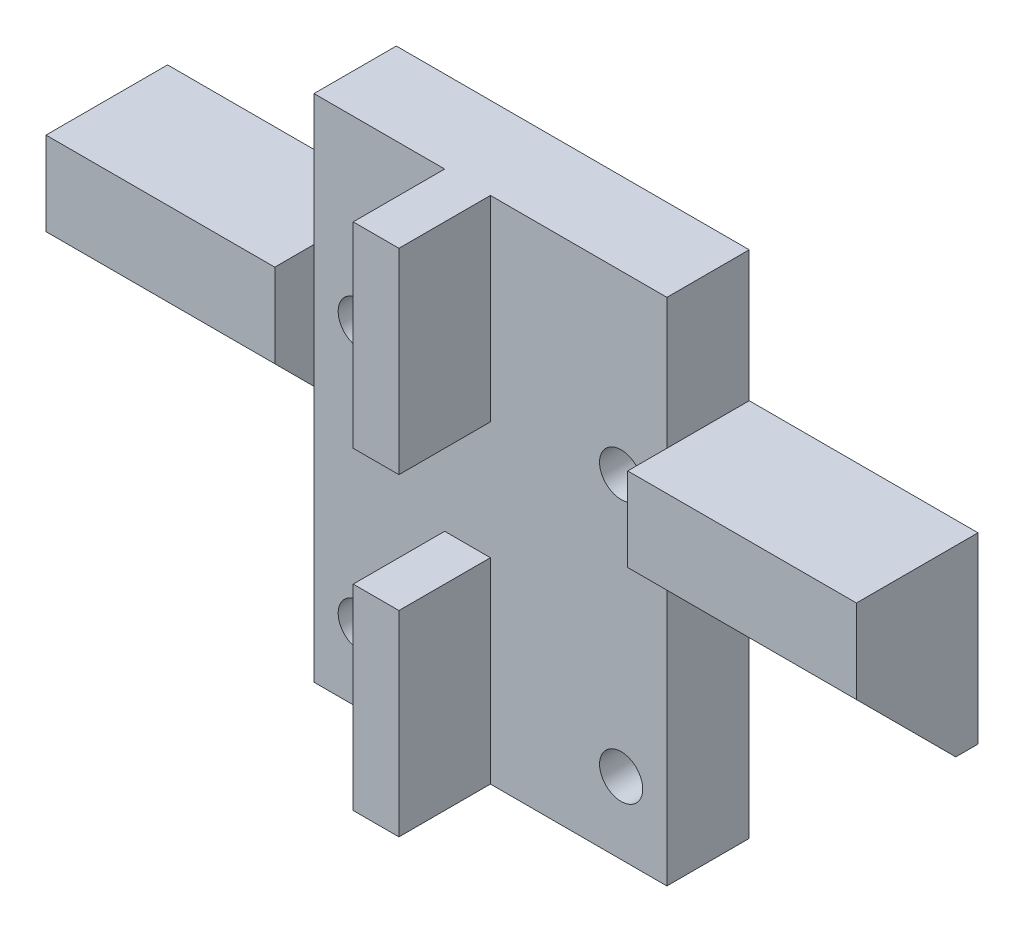
SolidWorks part; units mm, degrees
material "3.1355 (EN-AW 2024)"
ref_plane "Front" through (0, 0, 0) normal (0, 0, 1) x (1, 0, 0)
ref_plane "Top" through (0, 0, 0) normal (0, 1, 0) x (1, 0, 0)
ref_plane "Right" through (0, 0, 0) normal (1, 0, 0) x (0, 0, -1)
sketch "Эскиз1" plane through (0, 0, 0) normal (0, 0, 1) x (1, 0, 0)
  line L0 (-13.5, 23.5) -> (13.5, 23.5)
  line L1 (13.5, 23.5) -> (13.5, 13.5)
  line L2 (13.5, 13.5) -> (31, 13.5)
  line L3 (31, 13.5) -> (31, -0.5)
  line L4 (31, -0.5) -> (13.5, -0.5)
  line L5 (13.5, -0.5) -> (13.5, -15.5)
  line L6 (13.5, -15.5) -> (-13.5, -15.5)
  line L7 (-13.5, -15.5) -> (-13.5, -0.5)
  line L8 (-13.5, -0.5) -> (-31, -0.5)
  line L9 (-31, -0.5) -> (-31, 13.5)
  line L10 (-31, 13.5) -> (-13.5, 13.5)
  line L11 (-13.5, 13.5) -> (-13.5, 23.5)
  line L12 (-10, 10) -> (0, 10) construction
  line L13 (0, 10) -> (10, 10) construction
  line L14 (10, 10) -> (10, 0) construction
  line L15 (10, 0) -> (10, -10) construction
  circle A0 centre (-10, 10) radius 1.65
  circle A1 centre (10, 10) radius 1.65
  circle A2 centre (10, -10) radius 1.65
  circle A3 centre (-10, -10) radius 1.65
  point P12 (0, 23.5)
  point P14 (0, -15.5)
  dimension "D1" = 3.3
  dimension "D2" = 20
  dimension "D3" = 20
  dimension "D4" = 27
  dimension "D5" = 62
  dimension "D6" = 14
  dimension "D7" = 15
  dimension "D8" = 39
  dimension "D9" = 5.5
extrude "База" add sketch "Эскиз1" along normal blind 13.3
sketch "Эскиз2" plane through (0, 0, 13.3) normal (0, 0, 1) x (1, 0, 0)
  line L0 (0, 23.5) -> (13.5, 23.5)
  line L1 (13.5, 23.5) -> (-13.5, 23.5) construction
  line L2 (13.5, 23.5) -> (13.5, -15.5)
  line L3 (13.5, -15.5) -> (0, -15.5)
  line L4 (-13.5, -15.5) -> (13.5, -15.5) construction
  line L5 (0, -15.5) -> (0, -0.5)
  line L6 (0, -0.5) -> (-3.5, -0.5)
  line L7 (-3.5, -0.5) -> (-3.5, -15.5)
  line L8 (-3.5, -15.5) -> (-13.5, -15.5)
  line L9 (-13.5, -15.5) -> (-13.5, 23.5)
  line L10 (-13.5, 23.5) -> (-3.5, 23.5)
  line L11 (-3.5, 23.5) -> (-3.5, 8.5)
  line L12 (-3.5, 8.5) -> (0, 8.5)
  line L13 (0, 8.5) -> (0, 23.5)
  dimension "D1" = 3.5
  dimension "D2" = 15
extrude "ЗонаКаретки" cut sketch "Эскиз2" against normal blind 7
sketch "Эскиз3" plane through (0, 0, 13.3) normal (0, 0, 1) x (1, 0, 0)
  line L1 (-31, 13.5) -> (-13.5, 13.5)
  line L2 (-31, 13.5) -> (-31, -0.5)
  line L3 (-31, -0.5) -> (-13.5, -0.5)
  line L4 (-13.5, 13.5) -> (-13.5, -0.5)
  line L5 (13.5, 13.5) -> (31, 13.5)
  line L6 (13.5, 13.5) -> (13.5, -0.5)
  line L7 (13.5, -0.5) -> (31, -0.5)
  line L8 (31, 13.5) -> (31, -0.5)
extrude "ЗонаТяг" cut sketch "Эскиз3" against normal blind 4
sketch "Эскиз4" plane through (31, 0, 0) normal (1, 0, 0) x (0, 0, -1)
  line L0 (-9.3, 7.1) -> (-1.7, -0.5)
  line L1 (-9.3, -0.5) -> (-9.3, 13.5) construction
  line L2 (-6.3, -0.5) -> (0, -0.5) construction
  line L3 (-1.7, -0.5) -> (-9.3, -0.5)
  line L4 (-9.3, -0.5) -> (-9.3, 7.1)
  dimension "D1" = 7.6
  dimension "D2" = 7.6
extrude "СрезТягиR" cut sketch "Эскиз4" against normal up to surface (17.5 mm away) up to face at (13.5, 6.5, 7.8)
sketch "Эскиз5" plane through (-31, 0, 0) normal (-1, 0, 0) x (0, 0, 1)
  line L0 (9.3, 7.1) -> (9.3, -0.5)
  line L1 (9.3, -0.5) -> (1.7, -0.5)
  line L2 (1.7, -0.5) -> (9.3, 7.1)
extrude "СрезТягиL" cut sketch "Эскиз5" against normal up to surface (17.5 mm away) up to face at (-13.5, 6.5, 7.8)
sketch "Эскиз6" plane through (0, -1.1, 1.1) normal (0, -0.7071, 0.7071) x (1, 0, 0)
  line L0 (-23.605, 9.3485) -> (0, 9.3485) construction
  line L1 (0, 9.3485) -> (23.605, 9.3485) construction
  line L3 (-13.5, 0.8485) -> (-31, 0.8485) construction
  circle A0 centre (-23.605, 9.3485) radius 2
  circle A1 centre (23.605, 9.3485) radius 2
  dimension "D1" = 4
  dimension "D2" = 47.21
  dimension "D3" = 8.5
extrude "Вырез-Вытянуть5" cut sketch "Эскиз6" against normal blind 3.5
